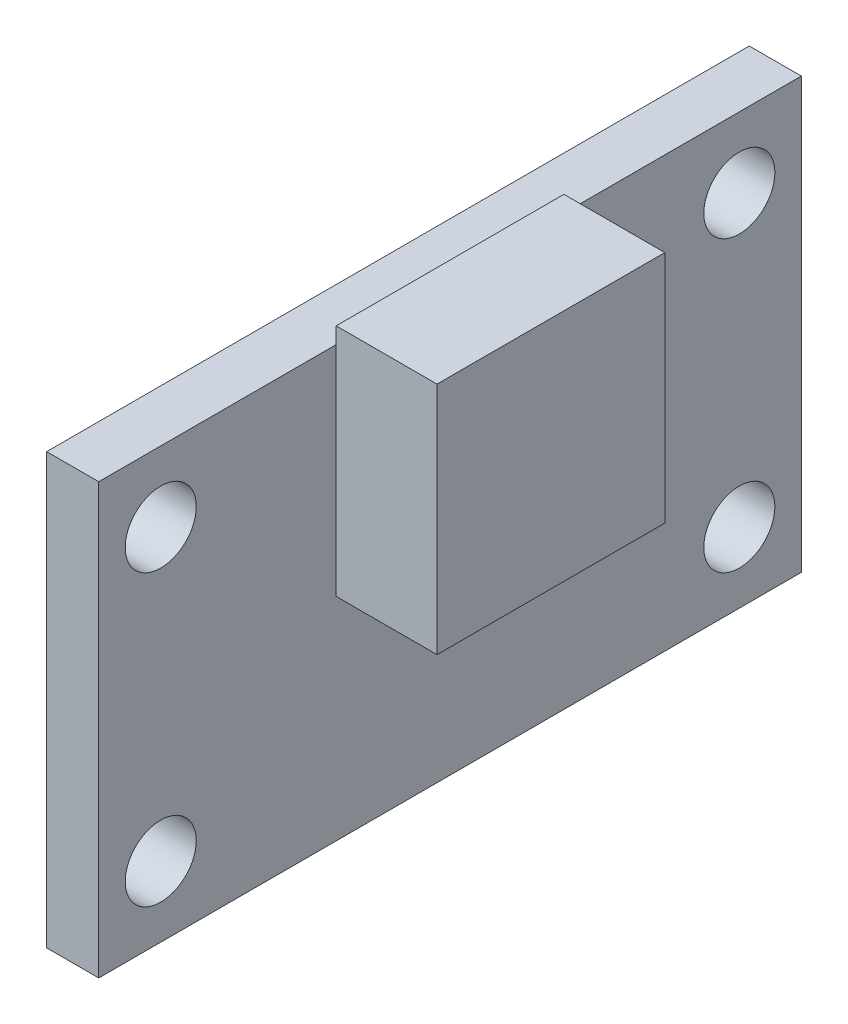
SolidWorks part; units mm, degrees
ref_plane "Front Plane" through (0, 0, 0) normal (0, 0, 1) x (1, 0, 0)
ref_plane "Top Plane" through (0, 0, 0) normal (0, 1, 0) x (1, 0, 0)
ref_plane "Right Plane" through (0, 0, 0) normal (1, 0, 0) x (0, 0, -1)
sketch "Sketch1" plane through (0, 0, 0) normal (1, 0, 0) x (0, 0, -1)
  line L1 (0, 0) -> (21.59, 0)
  line L2 (0, 0) -> (0, 13.208)
  line L3 (0, 13.208) -> (21.59, 13.208)
  line L4 (21.59, 0) -> (21.59, 13.208)
  dimension "D1" = 21.59
  dimension "D2" = 13.208
extrude "Boss-Extrude1" add sketch "Sketch1" along normal blind 1.6
hole_wizard "#44 (0.086) Diameter Hole1" positions "Sketch2" profile "Sketch3" hole size "#44" standard "ANSI Inch" end condition through all
sketch "Sketch2" plane through (1.6, 0, 0) normal (1, 0, 0) x (0, 0, -1)
  line L4 (0, 13.208) -> (0, 0) construction
  line L6 (0, 0) -> (21.59, 0) construction
  point P0 (1.905, 11.049)
  point P2 (19.685, 11.049)
  point P4 (19.685, 2.159)
  point P6 (1.905, 2.159)
  dimension "D1" = 17.78
  dimension "D2" = 17.78
  dimension "D3" = 8.89
  dimension "D4" = 1.905
  dimension "D5" = 2.159
sketch "Sketch3" plane through (1.6, 11.049, -1.905) normal (0, 1, 0) x (0, 0, -1)
  line L0 (0, 0) -> (0, 1.6)
  line L1 (0, 1.6) -> (1.0922, 1.6)
  line L2 (1.0922, 1.6) -> (1.0922, 0)
  line L5 (1.0922, 0) -> (0, 0)
  line L11 (0, -6.35) -> (0, 107.95) construction
  dimension "Thru Hole Dia." = 2.1844
  dimension "Thru Hole Depth" = 1.6
sketch "Sketch4" plane through (1.6, 0, 0) normal (1, 0, 0) x (0, 0, -1)
  line L0 (0, 13.208) -> (0, 0) construction
  line L1 (7.295, 6.508) -> (14.295, 6.508)
  line L2 (7.295, 6.508) -> (7.295, 13.708)
  line L3 (7.295, 13.708) -> (14.295, 13.708)
  line L4 (14.295, 6.508) -> (14.295, 13.708)
  line L5 (21.59, 13.208) -> (0, 13.208) construction
  dimension "D1" = 7
  dimension "D2" = 7.2
  dimension "D3" = 7.295
  dimension "D4" = 0.5
extrude "Boss-Extrude2" add sketch "Sketch4" along normal blind 3.1
equation "\"D5@Sketch2\"=((0.52in-0.35in)/2)"
equation "\"D3@Sketch4\"=(0.85in-7mm)/2"
